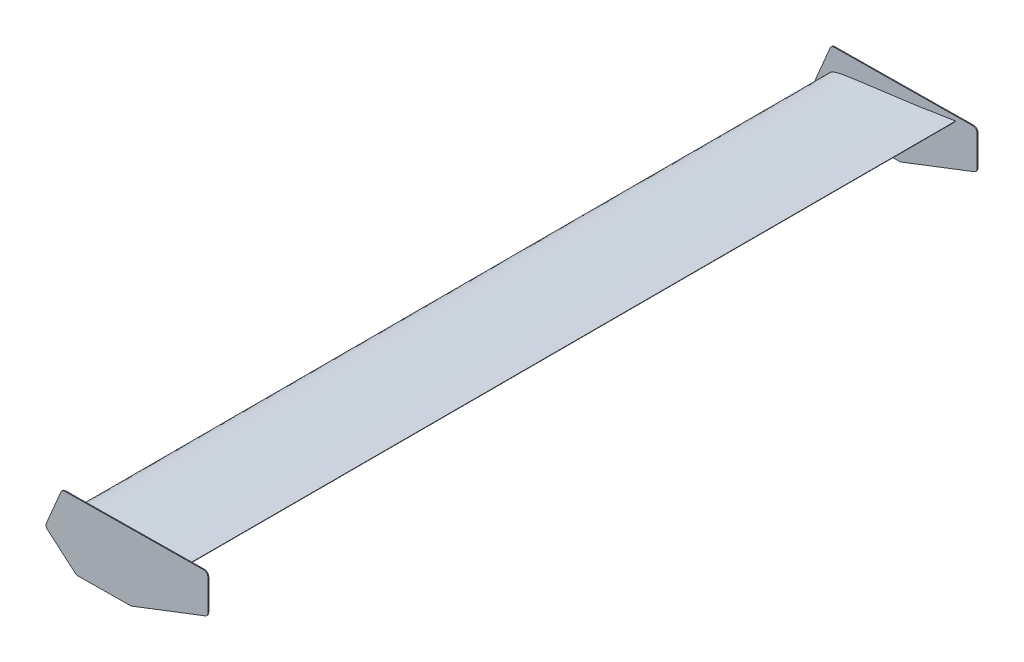
SolidWorks part; units mm, degrees
ref_plane "Front Plane" through (0, 0, 0) normal (0, 0, 1) x (1, 0, 0)
ref_plane "Top Plane" through (0, 0, 0) normal (0, 1, 0) x (1, 0, 0)
ref_plane "Right Plane" through (0, 0, 0) normal (1, 0, 0) x (0, 0, -1)
curve "Airfoil Curve"
  spline degree 3 poles (300, -0.39, 0) (295.0052, -1.7497, 0) (285.0396, -4.4626, 0) (265.0756, -9.3952, 0) (240.11, -14.8452, 0) (210.0811, -20.2176, 0) (180.0755, -24.6212, 0) (150.0532, -27.7624, 0) (120.0335, -29.7214, 0) (94.9726, -29.7413, 0) (74.963, -28.3569, 0) (59.9355, -26.5335, 0) (44.8755, -23.8445, 0) (32.3958, -20.6106, 0) (22.3952, -17.3445, 0) (14.8545, -14.2611, 0) (8.4203, -10.9265, 0) (2.8355, -6.9378, 0) (-2.0261, -0.5226, 0) (3.2214, 4.3836, 0) (8.5759, 6.3095, 0) (14.9528, 7.6093, 0) (22.4839, 8.2702, 0) (32.4958, 8.738, 0) (45.0031, 8.7029, 0) (60.0065, 8.2831, 0) (74.9993, 7.4837, 0) (94.9994, 6.5483, 0) (119.9952, 5.3479, 0) (150.0009, 4.2208, 0) (179.9969, 2.9692, 0) (209.9958, 1.9031, 0) (239.9971, 1.119, 0) (264.9992, 0.7209, 0) (284.9995, 0.4587, 0) (294.9999, 0.4129, 0) (300, 0.39, 0) knots 0 0 0 0 0.025305 0.050488 0.10052 0.150191 0.199587 0.24874 0.297716 0.346601 0.371103 0.395726 0.42057 0.445825 0.458702 0.47192 0.485786 0.493461 0.506863 0.516148 0.522766 0.535269 0.547551 0.559786 0.584229 0.608681 0.633151 0.657622 0.706558 0.755482 0.804406 0.85332 0.902221 0.951113 0.975557 1 1 1 1
ref_plane "Plane1" through (300, -0.39, 0) normal (-0.9649, -0.2627, 0) x (0, 0, 1)
sketch "AirfoilSketch" plane through (0, 0, 0) normal (0, 0, 1) x (1, 0, 0)
  line L2 (0, 0) -> (350.3559, 0) construction
  line B0 (295.4426, 52.0945) -> (295.577, 51.3262)
  line B1 (0, 0) -> (295.4426, 52.0945) construction
  spline B2 degree 3 poles (295.577, 51.3262) (290.8913, 49.1259) (281.5425, 44.7359) (262.7276, 36.4359) (239.075, 26.7642) (210.4216, 16.2963) (181.6242, 6.7865) (152.5926, -1.4825) (123.3599, -8.5867) (98.6776, -12.9259) (78.7288, -15.0113) (63.6119, -15.8054) (48.3139, -15.7525) (35.4635, -14.7181) (25.0496, -13.2247) (17.0903, -11.4872) (10.1777, -9.3116) (3.9889, -6.3452) (-1.9057, -0.864) (2.4176, 4.8732) (7.36, 7.6932) (13.4174, 10.0728) (20.7219, 12.0219) (30.5033, 14.2084) (42.8295, 16.3297) (57.6806, 18.5023) (72.5868, 20.2991) (92.4488, 22.8251) (117.2774, 25.9512) (147.0282, 30.0129) (176.791, 33.9504) (206.5246, 38.0712) (236.2121, 42.47) (260.9087, 46.3874) (280.6548, 49.5766) (290.5134, 51.2552) (295.4426, 52.0945) knots 0 0 0 0 0.025305 0.050488 0.10052 0.150191 0.199587 0.24874 0.297716 0.346601 0.371103 0.395726 0.42057 0.445825 0.458702 0.47192 0.485786 0.493461 0.506863 0.516148 0.522766 0.535269 0.547551 0.559786 0.584229 0.608681 0.633151 0.657622 0.706558 0.755482 0.804406 0.85332 0.902221 0.951113 0.975557 1 1 1 1
  dimension "AoA_Rear_Wing" = 10
sketch_block_instance "AirfoilBlock-1"
sketch_block "AirfoilBlock"
extrude "Rear Wing" add sketch "AirfoilSketch" along normal mid plane 1800
sketch "Endplate Sketch" plane through (0, 0, 900) normal (0, 0, 1) x (1, 0, 0)
  line L0 (4.1984, 59.4067) -> (-35.2909, -33.8505)
  line L1 (-35.2909, -33.8505) -> (38.2575, -96.7338)
  line L2 (4.1984, 59.4067) -> (345.6673, 62.9082)
  line L3 (345.6673, 62.9082) -> (345.6673, -26.3186)
  line L5 (38.2575, -96.7338) -> (166.2751, -95.4211)
  line L6 (166.2751, -95.4211) -> (345.6673, -26.3186)
  point P2 (152.1224, -101.9226)
  point P6 (313.3454, 63.1358)
  point P7 (345.6673, -26.3186)
  point P8 (345.6673, 62.9082)
  point P9 (4.1984, 59.4067)
  point P10 (-35.2909, -33.8505)
extrude "Endplate" add sketch "Endplate Sketch" along normal mid plane 2
fillet "Endplate Fillet" radius 10 6 edges at (345.6673, 62.9082, 900) (345.6673, -26.3186, 900) (166.2751, -95.4211, 900) (4.1984, 59.4067, 900) (-35.2909, -33.8505, 900) (38.2575, -96.7338, 900)
mirror "Mirror3" about plane through (0, 0, 0) normal (0, 0, 1) of "Endplate Fillet", "Endplate"
